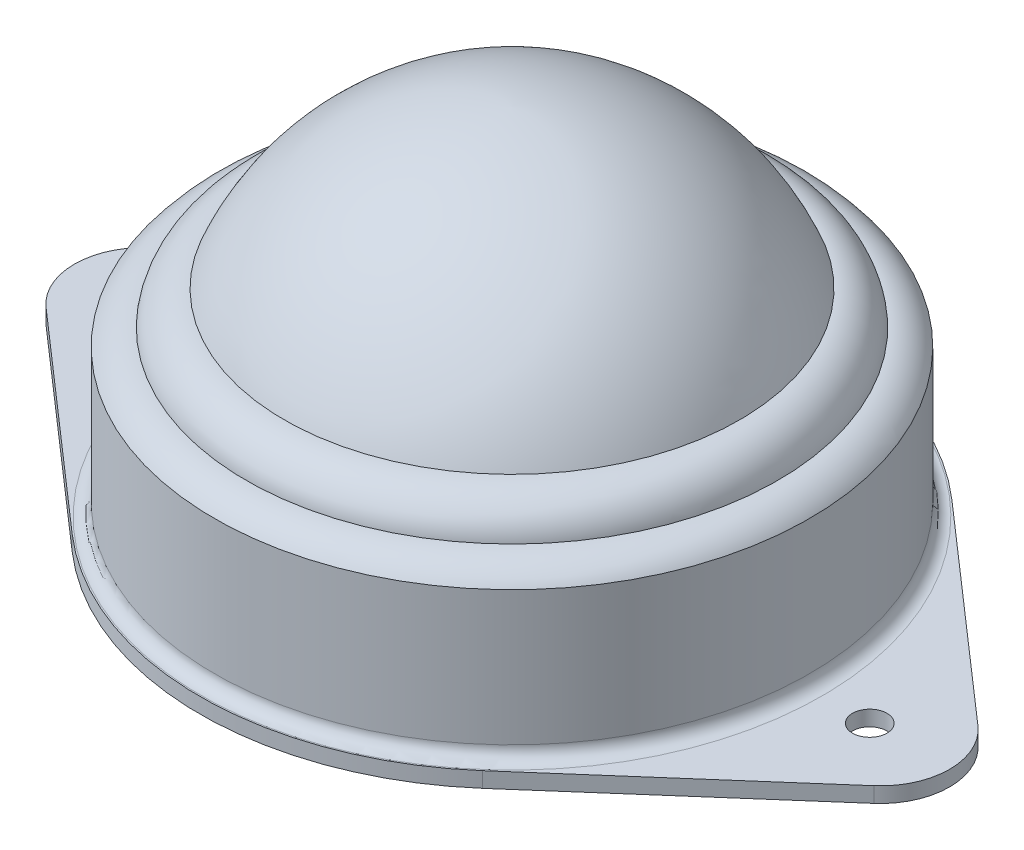
SolidWorks part; units mm, degrees
ref_plane "前视基准面" through (0, 0, 0) normal (0, 0, 1) x (1, 0, 0)
ref_plane "上视基准面" through (0, 0, 0) normal (0, 1, 0) x (1, 0, 0)
ref_plane "右视基准面" through (0, 0, 0) normal (1, 0, 0) x (0, 0, -1)
sketch "草图1" plane through (0, 0, 0) normal (0, 0, 1) x (1, 0, 0)
  line L2 (23.2911, 0) -> (0, 0)
  line L3 (0, 0) -> (0, 27.8)
  line L4 (23.2911, 11.5189) -> (23.2911, 0)
  arc A0 (23.2911, 11.5189) -> (20.7979, 12.8502) centre (20.7979, 9.8502) ccw
  arc A1 (20.7979, 12.8502) -> (17.8221, 15.4687) centre (17.8223, 12.4687) ccw
  arc A2 (17.8221, 15.4687) -> (0, 27.8) centre (-0.5659, 7.9375) ccw
revolve "旋转1" add sketch "草图1" angle 360 about L3
sketch "草图2" plane through (0, 0, 0) normal (0, -1, 0) x (1, 0, 0)
  line L0 (16.0693, -18.3613) -> (32.4063, -4.0636)
  line L1 (16.0693, 18.3613) -> (32.4063, 4.0636)
  line L2 (0, 0) -> (0, -45.4266) construction
  line L3 (-16.0693, 18.3613) -> (-32.4063, 4.0636)
  line L4 (-16.0693, -18.3613) -> (-32.4063, -4.0636)
  arc A0 (16.0693, 18.3613) -> (-16.0693, 18.3613) centre (0, 0) ccw
  arc A1 (32.4063, -4.0636) -> (32.4063, 4.0636) centre (28.85, 0) ccw
  arc A2 (-32.4063, -4.0636) -> (-32.4063, 4.0636) centre (-28.85, 0) cw
  arc A3 (-16.0693, -18.3613) -> (16.0693, -18.3613) centre (0, 0) ccw
  dimension "D1" = 28.85
extrude "凸台-拉伸1" add sketch "草图2" along normal blind 1.2
sketch "草图3" plane through (0, 0, 0) normal (0, 1, 0) x (1, 0, 0)
  line L0 (0, 0) -> (0, 15.9276) construction
  circle A0 centre (-28, 0) radius 1.35
  circle A1 centre (28, 0) radius 1.35
  dimension "D1" = 28
extrude "切除-拉伸1" cut sketch "草图3" against normal through all
fillet "圆角1" radius 1 1 edges at (0, 0, -23.2911)
